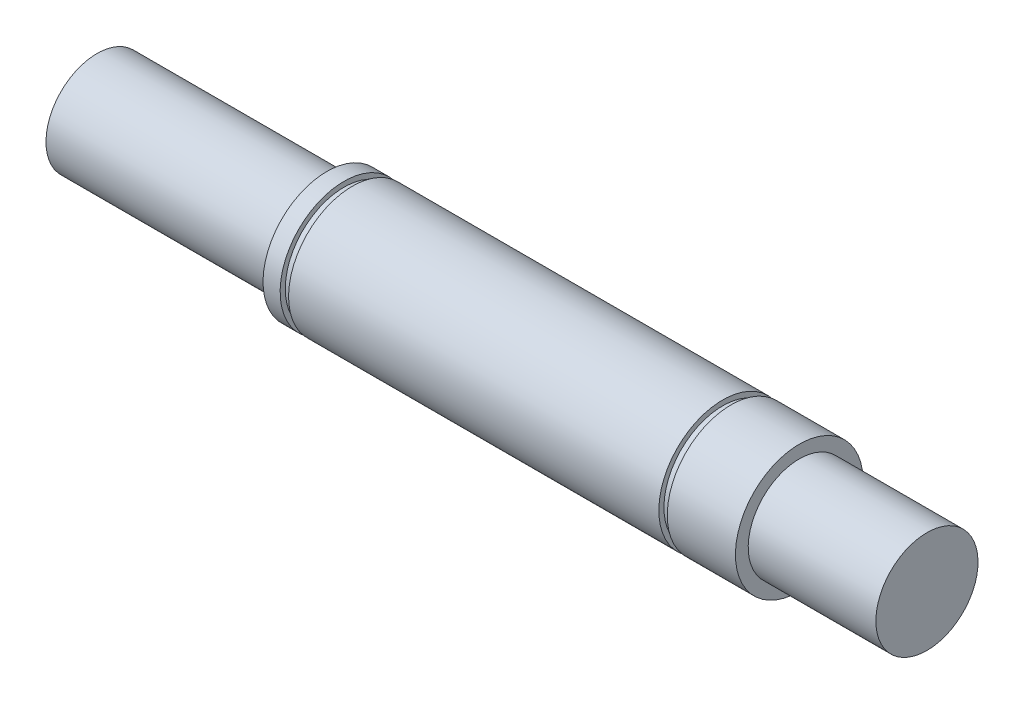
SolidWorks part; units mm, degrees
material "AISI 1020"
ref_plane "Front Plane" through (0, 0, 0) normal (0, 0, 1) x (1, 0, 0)
ref_plane "Top Plane" through (0, 0, 0) normal (0, 1, 0) x (1, 0, 0)
ref_plane "Right Plane" through (0, 0, 0) normal (1, 0, 0) x (0, 0, -1)
sketch "Sketch1" plane through (0, 0, 0) normal (0, 0, 1) x (1, 0, 0)
  line L0 (-145.4732, -1.2045) -> (-145.4732, 2.7955)
  line L1 (-145.4732, 2.7955) -> (-155.4732, 2.7955)
  line L10 (-160.8132, 3.7955) -> (-160.8132, 3.3955)
  line L11 (-160.8132, 3.3955) -> (-161.4732, 3.3955)
  line L12 (-161.4732, 3.3955) -> (-161.4732, 3.7955)
  line L13 (-161.4732, 3.7955) -> (-190.4732, 3.7955)
  line L14 (-190.4732, 3.7955) -> (-190.4732, 3.3955)
  line L15 (-190.4732, 3.3955) -> (-191.1332, 3.3955)
  line L16 (-191.1332, 3.3955) -> (-191.1332, 3.7955)
  line L17 (-191.1332, 3.7955) -> (-192.4732, 3.7955)
  line L18 (-155.4732, 2.7955) -> (-155.4732, 3.7955)
  line L20 (-192.4732, 3.7955) -> (-192.4732, 2.7955)
  line L21 (-192.4732, 2.7955) -> (-210.4732, 2.7955)
  line L22 (-210.4732, 2.7955) -> (-210.4732, -1.2045)
  line L23 (-210.4732, -1.2045) -> (-145.4732, -1.2045)
  line L37 (-160.8132, 3.7955) -> (-155.4732, 3.7955)
  point P2 (0, 0)
  point P3 (0, 0)
  point P5 (0, 0)
  point P6 (0, 0)
  dimension "D1" = 4
  dimension "D2" = 5
  dimension "D3" = 0.4
  dimension "D4" = 29
  dimension "D5" = 65
  dimension "D6" = 18
  dimension "D7" = 0.66
  dimension "D8" = 2
  dimension "D9" = 10
revolve "Revolve1" add sketch "Sketch1" angle 360 about L23
